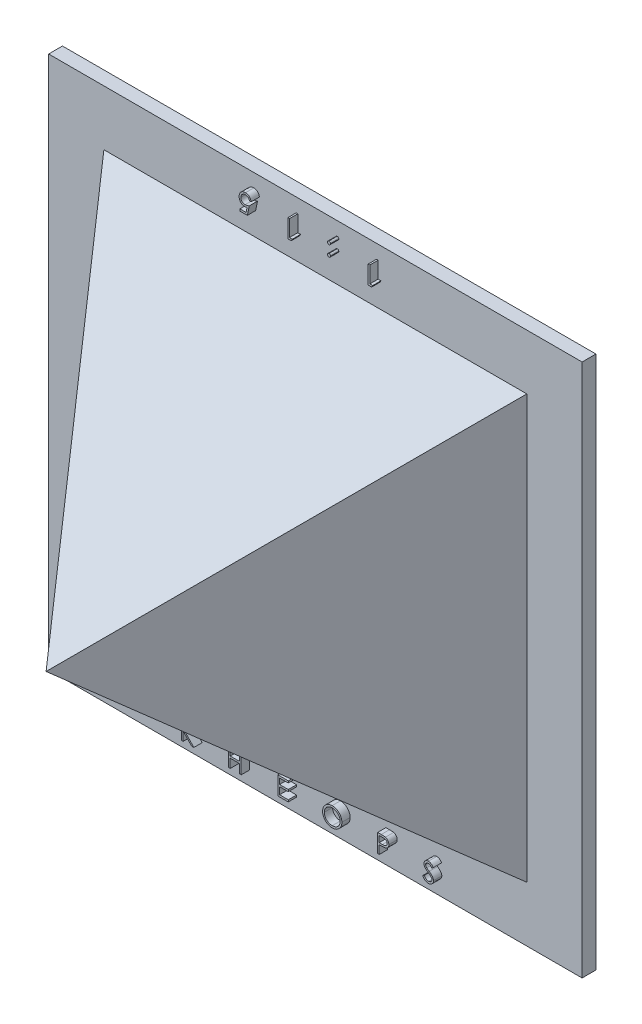
SolidWorks part; units mm, degrees
ref_plane "Plan de face" through (0, 0, 0) normal (0, 0, 1) x (1, 0, 0)
ref_plane "Plan de dessus" through (0, 0, 0) normal (0, 1, 0) x (1, 0, 0)
ref_plane "Plan de droite" through (0, 0, 0) normal (1, 0, 0) x (0, 0, -1)
sketch "Esquisse1" plane through (0, 0, 0) normal (0, 0, 1) x (1, 0, 0)
  line L1 (0, 0) -> (153, 0)
  line L2 (0, 0) -> (0, 153)
  line L3 (0, 153) -> (153, 153)
  line L4 (153, 0) -> (153, 153)
  dimension "D1" = 153
extrude "Boss.-Extru.1" add sketch "Esquisse1" along normal blind 97.7 draft 38.14
sketch "Esquisse3" plane through (0, 0, 0) normal (0, 0, -1) x (-1, 0, 0)
  line L8 (20, -20) -> (20, 173)
  line L9 (20, 173) -> (-173, 173)
  line L10 (-173, 173) -> (-173, -20)
  line L11 (-173, -20) -> (20, -20)
  line L12 (20, -20) -> (20, 173)
  line L13 (20, 173) -> (-173, 173)
  line L14 (-173, 173) -> (-173, -20)
  line L15 (-173, -20) -> (20, -20)
  dimension "D1" = 20
extrude "Boss.-Extru.3" add sketch "Esquisse3" along normal blind 5 separate body
sketch "Esquisse2" plane through (0, 0, -5) normal (0, 0, -1) x (-1, 0, 0)
  line L0 (0, 0) -> (-153, 0) construction
  line L1 (0, 153) -> (0, 0) construction
  circle A0 centre (-76.5, 76.5) radius 24
  point P5 (-76.5, 0)
  point P8 (0, 76.5)
  dimension "D1" = 48
extrude "Boss.-Extru.2" add sketch "Esquisse2" along normal blind 30
sketch "Esquisse4" plane through (0, 0, 0) normal (0, 0, 1) x (1, 0, 0)
  line L0 (30.2453, -15) -> (122.7547, -15) construction
  line L2 (173, -20) -> (-20, -20) construction
  line L3 (51.5, 168) -> (101.5, 168) construction
  line L6 (-20, 173) -> (173, 173) construction
  line L7 (153, 153) -> (0, 153) construction
  line L8 (0, 0) -> (153, 0) construction
  text T0 "KHEOPS" font "Century Gothic" height in points 25
  text T1 "1:15" font "Century Gothic" height in points 25
  point P4 (76.5, 0)
  point P5 (76.5, -15)
  point P15 (76.5, 153)
  point P16 (76.5, 168)
  dimension "D1" = 5
  dimension "D2" = 5
  dimension "D3" = 50
extrude "Boss.-Extru.4" add sketch "Esquisse4" along normal blind 3
